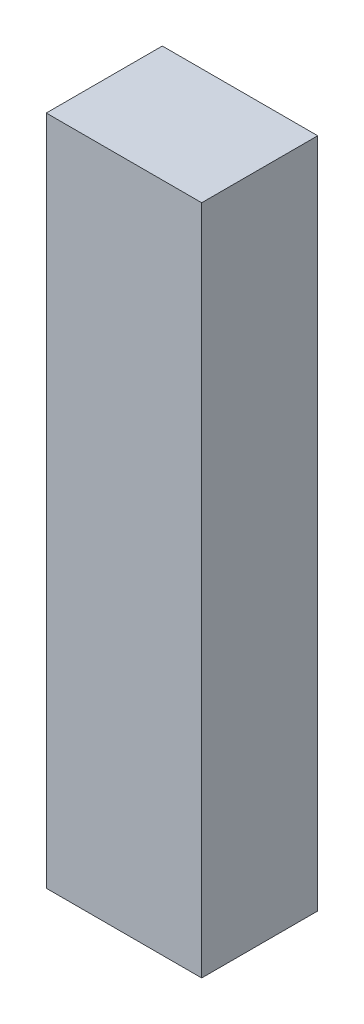
SolidWorks part; units mm, degrees
ref_plane "Front Plane" through (0, 0, 0) normal (0, 0, 1) x (1, 0, 0)
ref_plane "Top Plane" through (0, 0, 0) normal (0, 1, 0) x (1, 0, 0)
ref_plane "Right Plane" through (0, 0, 0) normal (1, 0, 0) x (0, 0, -1)
sketch "Sketch1" plane through (0, 0, 0) normal (0, 1, 0) x (1, 0, 0)
  line L0 (-27.8321, 19.4041) -> (30.9681, 19.4041)
  line L1 (30.9681, 19.4041) -> (30.9681, -24.5001)
  line L2 (30.9681, -24.5001) -> (-27.8321, -24.5001)
  line L3 (-27.8321, -24.5001) -> (-27.8321, 19.4041)
extrude "Boss-Extrude1" add sketch "Sketch1" along normal blind 254
